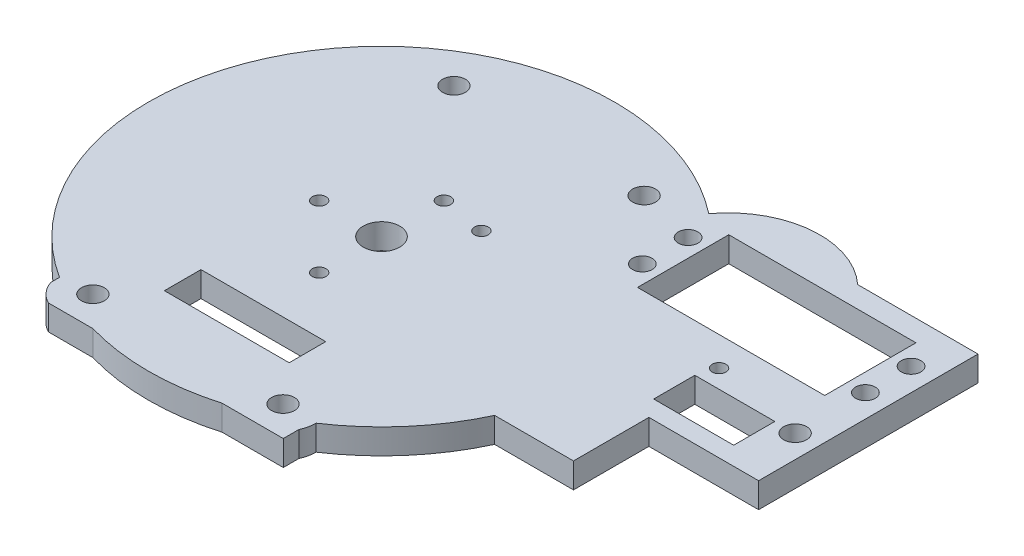
SolidWorks part; units mm, degrees
ref_plane "Alzado" through (0, 0, 0) normal (0, 0, 1) x (1, 0, 0)
ref_plane "Planta" through (0, 0, 0) normal (0, 1, 0) x (1, 0, 0)
ref_plane "Vista lateral" through (0, 0, 0) normal (1, 0, 0) x (0, 0, -1)
sketch "Croquis1" plane through (0, 0, 0) normal (0, 1, 0) x (1, 0, 0)
  line L1 (-57.5, 50) -> (57.5, 50)
  line L2 (-57.5, 50) -> (-57.5, -50)
  line L3 (-57.5, -50) -> (57.5, -50)
  line L4 (57.5, 50) -> (57.5, -50)
  line L5 (-57.5, 50) -> (57.5, -50) construction
  line L6 (-57.5, -50) -> (57.5, 50) construction
  point P0 (0, 0)
extrude "Saliente-Extruir1" add sketch "Croquis1" along normal blind 5.5
sketch "Croquis2" plane through (0, 5.5, 0) normal (0, 1, 0) x (1, 0, 0)
  line L0 (57.5, 50) -> (-57.5, 50) construction
  line L1 (-57.5, 50) -> (-57.5, -50) construction
  circle A0 centre (-50.65, 43.5) radius 2.5
  circle A1 centre (-9.05, 43.5) radius 2.5
  dimension "D1" = 6.5
  dimension "D2" = 6.5
  dimension "D5" = 5
  dimension "D6" = 5
  dimension "D3" = 6.85
  dimension "D4" = 41.6
extrude "Cortar-Extruir1" cut sketch "Croquis2" against normal blind 5.5
sketch "Croquis3" plane through (0, 5.5, 0) normal (0, 1, 0) x (1, 0, 0)
  circle A0 centre (-50.65, -35.5) radius 2.5
  circle A1 centre (-9.05, -35.5) radius 2.5
  circle A2 centre (-50.65, 43.5) radius 2.5 construction
  circle A3 centre (-9.05, 43.5) radius 2.5 construction
  dimension "D1" = 79
  dimension "D2" = 79
extrude "Cortar-Extruir2" cut sketch "Croquis3" against normal blind 5.5
sketch "Croquis4" plane through (0, 5.5, 0) normal (0, 1, 0) x (1, 0, 0)
  line L0 (-57.5, -50) -> (57.5, -50) construction
  line L1 (-43.5, -28.3777) -> (-17.5, -28.3777)
  line L2 (-43.5, -28.3777) -> (-43.5, -35.5)
  line L3 (-43.5, -35.5) -> (-17.5, -35.5)
  line L4 (-17.5, -28.3777) -> (-17.5, -35.5)
  line L5 (-57.5, 50) -> (-57.5, -50) construction
  dimension "D1" = 14.5
  dimension "D2" = 21.6223
  dimension "D3" = 14
  dimension "D4" = 40
extrude "Cortar-Extruir3" cut sketch "Croquis4" against normal blind 5.5
sketch "Croquis5" plane through (0, 5.5, 0) normal (0, 1, 0) x (1, 0, 0)
  line L0 (-43.5, -35.5) -> (-17.5, -35.5) construction
  line L1 (-24.3302, -35.5) -> (-16.2, -35.5)
  line L2 (-24.3302, -35.5) -> (-24.3302, -28.3777)
  line L3 (-24.3302, -28.3777) -> (-16.2, -28.3777)
  line L4 (-16.2, -35.5) -> (-16.2, -28.3777)
  line L5 (-17.5, -28.3777) -> (-43.5, -28.3777) construction
  circle A0 centre (-9.05, -35.5) radius 2.5 construction
  dimension "D2" = 7.15
  dimension "D1" = 0
extrude "Cortar-Extruir4" cut sketch "Croquis5" against normal blind 5.5
sketch "Croquis6" plane through (0, 5.5, 0) normal (0, 1, 0) x (1, 0, 0)
  line L0 (-57.5, 50) -> (-57.5, -50) construction
  line L1 (57.5, 50) -> (-57.5, 50) construction
  circle A0 centre (-30, 7.21) radius 4
  dimension "D1" = 8
  dimension "D2" = 27.5
  dimension "D3" = 42.79
extrude "Cortar-Extruir5" cut sketch "Croquis6" against normal blind 5.5
sketch "Croquis7" plane through (0, 5.5, 0) normal (0, 1, 0) x (1, 0, 0)
  circle A0 centre (-43.64, 7.21) radius 1.5
  circle A1 centre (-16.36, 7.21) radius 1.5
  circle A2 centre (-30, -6.43) radius 1.5
  circle A3 centre (-30, 7.21) radius 4 construction
  circle A4 centre (-30, 20.85) radius 1.5
  dimension "D1" = 13.64
  dimension "D4" = 13.64
  dimension "D2" = 13.64
  dimension "D3" = 13.64
extrude "Cortar-Extruir6" cut sketch "Croquis7" against normal blind 10
sketch "Croquis8" plane through (0, 5.5, 0) normal (0, 1, 0) x (1, 0, 0)
  line L0 (57.5, 50) -> (-57.5, 50) construction
  line L1 (-43.5, -27) -> (-16.2, -27)
  line L2 (-43.5, -27) -> (-43.5, -19)
  line L3 (-43.5, -19) -> (-16.2, -19)
  line L4 (-16.2, -27) -> (-16.2, -19)
  line L5 (-43.5, -28.3777) -> (-43.5, -35.5) construction
  line L6 (-16.2, -35.5) -> (-16.2, -28.3777) construction
  dimension "D1" = 69
  dimension "D2" = 77
  dimension "D3" = 0
  dimension "D4" = 0
extrude "Cortar-Extruir7" cut sketch "Croquis8" against normal blind 5.5
sketch "Croquis9" plane through (0, 5.5, 0) normal (0, 1, 0) x (1, 0, 0)
  line L1 (-43.5, -35.5) -> (-16.2, -35.5)
  line L2 (-43.5, -35.5) -> (-43.5, -28.3777)
  line L3 (-43.5, -28.3777) -> (-16.2, -28.3777)
  line L4 (-16.2, -35.5) -> (-16.2, -28.3777)
extrude "Saliente-Extruir3" add sketch "Croquis9" against normal blind 5.5
sketch "Croquis10" plane through (0, 5.5, 0) normal (0, 1, 0) x (1, 0, 0)
  line L1 (-20.1749, 15.63) -> (-11.3068, 15.63)
  line L2 (-20.1749, 15.63) -> (-20.1749, -1.4411)
  line L3 (-20.1749, -1.4411) -> (-11.3068, -1.4411)
  line L4 (-11.3068, 15.63) -> (-11.3068, -1.4411)
extrude "Saliente-Extruir4" add sketch "Croquis10" against normal blind 5.5
sketch "Croquis11" plane through (0, 5.5, 0) normal (0, 1, 0) x (1, 0, 0)
  line L0 (57.5, 50) -> (-57.5, 50) construction
  circle A0 centre (-30, 7) radius 4
  circle A1 centre (-30, 7.21) radius 4 construction
  circle A2 centre (-30, 7.21) radius 4
  circle M9 centre (-30, 7.21) radius 4
  dimension "D1" = 0
  dimension "D3" = 8
  dimension "D2" = 43
extrude "Saliente-Extruir5" add sketch "Croquis11" against normal blind 5.5 contours A0 M9
sketch "Croquis12" plane through (0, 5.5, 0) normal (0, 1, 0) x (1, 0, 0)
  circle A0 centre (-30, 7) radius 4
extrude "Cortar-Extruir10" cut sketch "Croquis12" against normal blind 5.5
sketch "Croquis13" plane through (0, 5.5, 0) normal (0, 1, 0) x (1, 0, 0)
  line L1 (-37.7409, 27.7091) -> (-22.8701, 27.7091)
  line L2 (-37.7409, 27.7091) -> (-37.7409, 15.6981)
  line L3 (-37.7409, 15.6981) -> (-22.8701, 15.6981)
  line L4 (-22.8701, 27.7091) -> (-22.8701, 15.6981)
  line L5 (-38.7704, -14.2721) -> (-20.5823, -14.2721)
  line L6 (-38.7704, -14.2721) -> (-38.7704, -2.9475)
  line L7 (-38.7704, -2.9475) -> (-20.5823, -2.9475)
  line L8 (-20.5823, -14.2721) -> (-20.5823, -2.9475)
extrude "Saliente-Extruir6" add sketch "Croquis13" against normal blind 5.5
sketch "Croquis14" plane through (0, 5.5, 0) normal (0, 1, 0) x (1, 0, 0)
  circle A0 centre (-30, 20.64) radius 1.5
  circle A1 centre (-30, -6.64) radius 1.5
  circle A2 centre (-30, 7) radius 4 construction
  dimension "D1" = 3
  dimension "D2" = 0
  dimension "D3" = 3
  dimension "D4" = 0
  dimension "D5" = 13.64
  dimension "D6" = 13.64
extrude "Cortar-Extruir11" cut sketch "Croquis14" against normal blind 5.5
sketch "Croquis15" plane through (0, 5.5, 0) normal (0, 1, 0) x (1, 0, 0)
  line L1 (-49.2086, 13.833) -> (-38.3148, 13.833)
  line L2 (-49.2086, 13.833) -> (-49.2086, 3.6201)
  line L3 (-49.2086, 3.6201) -> (-38.3148, 3.6201)
  line L4 (-38.3148, 13.833) -> (-38.3148, 3.6201)
extrude "Saliente-Extruir7" add sketch "Croquis15" against normal blind 5.5
sketch "Croquis16" plane through (0, 5.5, 0) normal (0, 1, 0) x (1, 0, 0)
  circle A0 centre (-43.64, 7) radius 1.5
  circle A1 centre (-30, 7) radius 4 construction
  dimension "D1" = 13.64
  dimension "D2" = 0
  dimension "D3" = 3
extrude "Cortar-Extruir12" cut sketch "Croquis16" against normal blind 5.5
sketch "Croquis17" plane through (0, 5.5, 0) normal (0, 1, 0) x (1, 0, 0)
  line L0 (57.5, -50) -> (57.5, 50) construction
  line L1 (57.5, 50) -> (-57.5, 50) construction
  circle A0 centre (52.5, 15) radius 2.5
  dimension "D1" = 5
  dimension "D2" = 35
extrude "Cortar-Extruir14" cut sketch "Croquis17" against normal blind 5.5
sketch "Croquis18" plane through (0, 5.5, 0) normal (0, 1, 0) x (1, 0, 0)
  line L1 (48.05, 15) -> (30.55, 15)
  line L2 (48.05, 15) -> (48.05, 6)
  line L3 (48.05, 6) -> (30.55, 6)
  line L4 (30.55, 15) -> (30.55, 6)
  circle A0 centre (52.5, 15) radius 2.5 construction
  dimension "D2" = 4.45
  dimension "D1" = 0
  dimension "D3" = 17.5
  dimension "D4" = 9
extrude "Cortar-Extruir16" cut sketch "Croquis18" against normal blind 5.5
sketch "Croquis19" plane through (0, 5.5, 0) normal (0, 1, 0) x (1, 0, 0)
  line L0 (57.5, -50) -> (57.5, 50) construction
  line L3 (57.5, 50) -> (-57.5, 50) construction
  line L4 (-57.5, 50) -> (-57.5, -50) construction
  circle A0 centre (31.85, 19) radius 1.5
  circle A1 centre (-20.15, 19) radius 1.5
  dimension "D1" = 25.65
  dimension "D2" = 31
  dimension "D3" = 3
  dimension "D4" = 37.35
  dimension "D5" = 31
  dimension "D6" = 3
extrude "Cortar-Extruir17" cut sketch "Croquis19" against normal blind 5.5
sketch "Croquis20" plane through (0, 5.5, 0) normal (0, 1, 0) x (1, 0, 0)
  line L0 (57.5, -50) -> (57.5, 50) construction
  line L1 (57.5, 50) -> (-57.5, 50) construction
  circle A0 centre (52.5, 40.36) radius 2.15
  circle A1 centre (52.5, 30.36) radius 2.15
  circle A2 centre (3.71, 40.36) radius 2.15
  circle A3 centre (3.71, 30.36) radius 2.15
  dimension "D1" = 5
  dimension "D5" = 4.3
  dimension "D6" = 4.3
  dimension "D7" = 4.3
  dimension "D8" = 4.3
  dimension "D2" = 5
  dimension "D3" = 53.79
  dimension "D4" = 53.79
  dimension "D9" = 9.64
  dimension "D10" = 9.64
  dimension "D11" = 19.64
  dimension "D12" = 19.64
extrude "Cortar-Extruir18" cut sketch "Croquis20" against normal blind 10
sketch "Croquis21" plane through (0, 5.5, 0) normal (0, 1, 0) x (1, 0, 0)
  line L0 (57.5, 50) -> (-57.5, 50) construction
  line L1 (7.63, 25.38) -> (48.58, 25.38)
  line L2 (7.63, 25.38) -> (7.63, 45.34)
  line L3 (7.63, 45.34) -> (48.58, 45.34)
  line L4 (48.58, 25.38) -> (48.58, 45.34)
  line L5 (57.5, -50) -> (57.5, 50) construction
  dimension "D1" = 24.62
  dimension "D2" = 4.66
  dimension "D3" = 49.87
  dimension "D4" = 8.92
extrude "Cortar-Extruir19" cut sketch "Croquis21" against normal blind 10
sketch "Croquis22" plane through (0, 5.5, 0) normal (0, 1, 0) x (1, 0, 0)
  line L0 (30.55, 6) -> (48.05, 6) construction
  line L1 (57.5, -50) -> (33.5, -50)
  line L2 (57.5, -50) -> (57.5, 2)
  line L3 (57.5, 2) -> (33.5, 2)
  line L4 (33.5, -50) -> (33.5, 2)
  dimension "D1" = 4
extrude "Cortar-Extruir20" cut sketch "Croquis22" against normal blind 20
sketch "Croquis23" plane through (0, 5.5, 0) normal (0, 1, 0) x (1, 0, 0)
  line L0 (33.5, 2) -> (33.5, -50) construction
  line L1 (-57.5, -50) -> (33.5, -50)
  line L2 (-57.5, -50) -> (-57.5, -42)
  line L3 (-57.5, -42) -> (33.5, -42)
  line L4 (33.5, -50) -> (33.5, -42)
  circle A0 centre (-30, 7) radius 51
  line M1 (33.5, -50) -> (33.5, 2)
  line M5 (-57.5, 50) -> (-57.5, -50)
  line M6 (-57.5, -50) -> (33.5, -50)
  dimension "D1" = 102
extrude "Cortar-Extruir21" cut sketch "Croquis23" against normal blind 20 contours A0 L3 M5 M6 M1
sketch "Croquis24" plane through (0, 5.5, 0) normal (0, 1, 0) x (1, 0, 0)
  line L0 (33.5, 2) -> (33.5, -42) construction
  line L1 (33.5, -14.5) -> (-5.1481, -14.5)
  line L2 (33.5, -14.5) -> (33.5, 0.8343)
  line L3 (33.5, 0.8343) -> (-5.1481, 0.8343)
  line L4 (-5.1481, -14.5) -> (-5.1481, 0.8343)
  circle A0 centre (-50.65, -35.5) radius 7.25
  circle A1 centre (-9.05, -35.5) radius 7.25
  circle A2 centre (-30, 7) radius 51
  line M29 (-15.8579, -42) -> (33.5, -42)
  line M30 (33.5, -42) -> (33.5, 2)
  line M34 (-57.5, 50) -> (-57.5, -42)
  line M35 (-57.5, -42) -> (-44.1421, -42)
  dimension "D1" = 21
extrude "Cortar-Extruir23" cut sketch "Croquis24" against normal blind 20 contours A0 M34 M35 | A2 A0 M35 | A2 A1 M29 | A2 A1 L1 M29 M30
sketch "Croquis25" plane through (0, 5.5, 0) normal (0, 1, 0) x (1, 0, 0)
  line L0 (-53.8613, -42) -> (-47.4387, -42) construction
  line L1 (-48.6972, -42) -> (-10.5962, -42)
  line L2 (-48.6972, -42) -> (-48.6972, -40.1673)
  line L3 (-48.6972, -40.1673) -> (-10.5962, -40.1673)
  line L4 (-10.5962, -42) -> (-10.5962, -40.1673)
extrude "Saliente-Extruir9" add sketch "Croquis25" against normal blind 5.5
sketch "Croquis26" plane through (0, 5.5, 0) normal (0, 1, 0) x (1, 0, 0)
  line L0 (-15.8579, -42) -> (-5.8387, -42) construction
  line L1 (-7.3056, -42) -> (-2.4887, -42)
  line L2 (-7.3056, -42) -> (-7.3056, -37.3911)
  line L3 (-7.3056, -37.3911) -> (-2.4887, -37.3911)
  line L4 (-2.4887, -42) -> (-2.4887, -37.3911)
  dimension "D1" = 3.35
extrude "Saliente-Extruir10" add sketch "Croquis26" against normal blind 5.5
sketch "Croquis27" plane through (0, 5.5, 0) normal (0, 1, 0) x (1, 0, 0)
  line L0 (-57.5, 50) -> (-57.5, -35.9506)
  line L1 (-57.5, 50) -> (-57.5, -37.8749) construction
  line L2 (-57.5, 50) -> (-2.5774, 50)
  line L3 (57.5, 50) -> (-57.5, 50) construction
  circle A0 centre (-30, 7) radius 51
  line M9 (57.5, 50) -> (-57.5, 50)
extrude "Saliente-Extruir11" add sketch "Croquis27" against normal blind 5.5 contours L0 A0 | A0 M9
sketch "Croquis28" plane through (0, 5.5, 0) normal (0, 1, 0) x (1, 0, 0)
  line L0 (48.58, 45.34) -> (7.63, 45.34) construction
  line L2 (7.63, 45.34) -> (7.63, 25.38) construction
  line L3 (4.0191, 50) -> (31.1809, 50)
  line L4 (57.5, 50) -> (-2.5774, 50) construction
  circle A0 centre (17.6, 35.25) radius 20.05
  line M9 (57.5, 50) -> (-2.5774, 50)
  dimension "D1" = 10.09
  dimension "D3" = 40.1
  dimension "D2" = 9.97
extrude "Saliente-Extruir12" add sketch "Croquis28" against normal blind 5.5 contours A0 M9
sketch "Croquis29" plane through (0, 5.5, 0) normal (0, 1, 0) x (1, 0, 0)
  line L0 (-2.5774, 50) -> (4.0191, 50)
  circle A0 centre (-30, 7) radius 51
  circle A1 centre (17.6, 35.25) radius 20.05
  line M11 (4.0191, 50) -> (-2.5774, 50)
extrude "Cortar-Extruir24" cut sketch "Croquis29" against normal blind 5.5 contours A1 A0 M11
